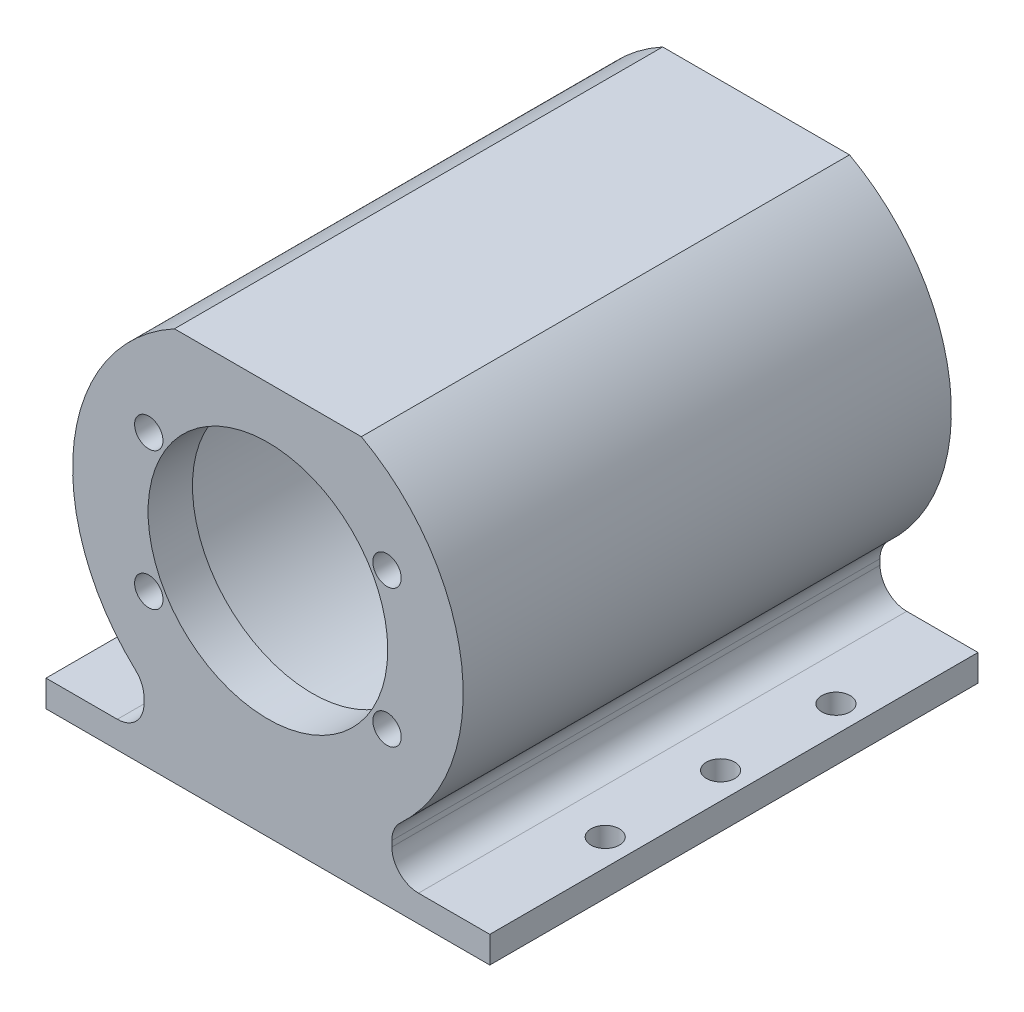
SolidWorks part; units mm, degrees
ref_plane "Front Plane" through (0, 0, 0) normal (0, 0, 1) x (1, 0, 0)
ref_plane "Top Plane" through (0, 0, 0) normal (0, 1, 0) x (1, 0, 0)
ref_plane "Right Plane" through (0, 0, 0) normal (1, 0, 0) x (0, 0, -1)
sketch "Çizim1" plane through (0, 0, 0) normal (0, 0, 1) x (1, 0, 0)
  line L0 (-13.9642, 6.5) -> (-13.9642, 1.5)
  line L1 (-25, -1.5) -> (25, -1.5)
  line L2 (-25, -1.5) -> (-25, 1.5)
  line L3 (-25, 1.5) -> (25, 1.5)
  line L4 (25, -1.5) -> (25, 1.5)
  line L5 (-25, -1.5) -> (25, 1.5) construction
  line L6 (-25, 1.5) -> (25, -1.5) construction
  line L7 (13.9642, 6.5) -> (13.9642, 1.5)
  line L8 (-10.5287, 42.817) -> (10.5287, 42.817)
  circle A0 centre (0, 23.5) radius 22
  circle A1 centre (0, 23.5) radius 18.65
  point P0 (0, 0)
  point P8 (-25, 0)
  dimension "D3" = 44
  dimension "D4" = 25
  dimension "D5" = 25
  dimension "D6" = 37.3
  dimension "D1" = 50
  dimension "D2" = 3
  dimension "D7" = 5
  dimension "D8" = 5
extrude "Yükseklik-Ekstrüzyon4" add sketch "Çizim1" along normal blind 55 contours L8 A0 A1 | L1 L4 L3 L2 | A0 L0 L3 | A0 L3 L7
fillet "Radyus1" radius 3 2 edges at (13.9642, 1.5, 27.5) (13.9642, 6.5, 27.5)
fillet "Radyus2" radius 3 2 edges at (-13.9642, 1.5, 27.5) (-13.9642, 6.5, 27.5)
sketch "Çizim7" plane through (0, 1.5, 0) normal (0, 1, 0) x (1, 0, 0)
  line L0 (-25, 0) -> (-16.9642, 0) construction
  line L1 (-25, -55) -> (-25, 0) construction
  circle A0 centre (-22, -13) radius 1.6
  circle A1 centre (-22, -26) radius 1.6
  circle A2 centre (-22, -39) radius 1.6
  dimension "D1" = 3.2
  dimension "D2" = 3.2
  dimension "D3" = 3.2
  dimension "D4" = 13
  dimension "D5" = 3
  dimension "D6" = 3
  dimension "D7" = 13
  dimension "D8" = 13
  dimension "D9" = 3
extrude "Kes-Ekstrüzyon1" cut sketch "Çizim7" against normal blind 55
sketch "Çizim8" plane through (0, 1.5, 0) normal (0, 1, 0) x (1, 0, 0)
  line L0 (25, -55) -> (25, 0) construction
  line L1 (16.9642, 0) -> (25, 0) construction
  circle A0 centre (22, -13) radius 1.6
  circle A1 centre (22, -26) radius 1.6
  circle A2 centre (22, -39) radius 1.6
  dimension "D1" = 3.2
  dimension "D2" = 3
  dimension "D3" = 13
  dimension "D4" = 13
  dimension "D5" = 3
  dimension "D6" = 3.2
  dimension "D7" = 3
  dimension "D8" = 13
  dimension "D9" = 3.2
extrude "Kes-Ekstrüzyon2" cut sketch "Çizim8" against normal blind 55
sketch "Çizim10" plane through (0, 0, 55) normal (0, 0, 1) x (1, 0, 0)
  circle A1 centre (0, 23.5) radius 13.5
  circle A2 centre (0, 23.5) radius 18.65 construction
  circle A3 centre (0, 23.5) radius 18.65
  circle A4 centre (-13.42, 31.25) radius 1.6
  circle A5 centre (-13.42, 15.75) radius 1.6
  circle A6 centre (13.42, 31.25) radius 1.6
  circle A7 centre (13.42, 15.75) radius 1.6
  dimension "D1" = 27
  dimension "D2" = 0
  dimension "D3" = 37.3
  dimension "D4" = 7.75
  dimension "D5" = 13.42
  dimension "D6" = 13.42
  dimension "D7" = 7.75
  dimension "D8" = 3.2
  dimension "D9" = 3.2
  dimension "D10" = 3.2
  dimension "D11" = 13.42
  dimension "D12" = 7.75
  dimension "D13" = 13.42
  dimension "D14" = 7.75
  dimension "D15" = 3.2
extrude "Yükseklik-Ekstrüzyon5" add sketch "Çizim10" against normal blind 5
